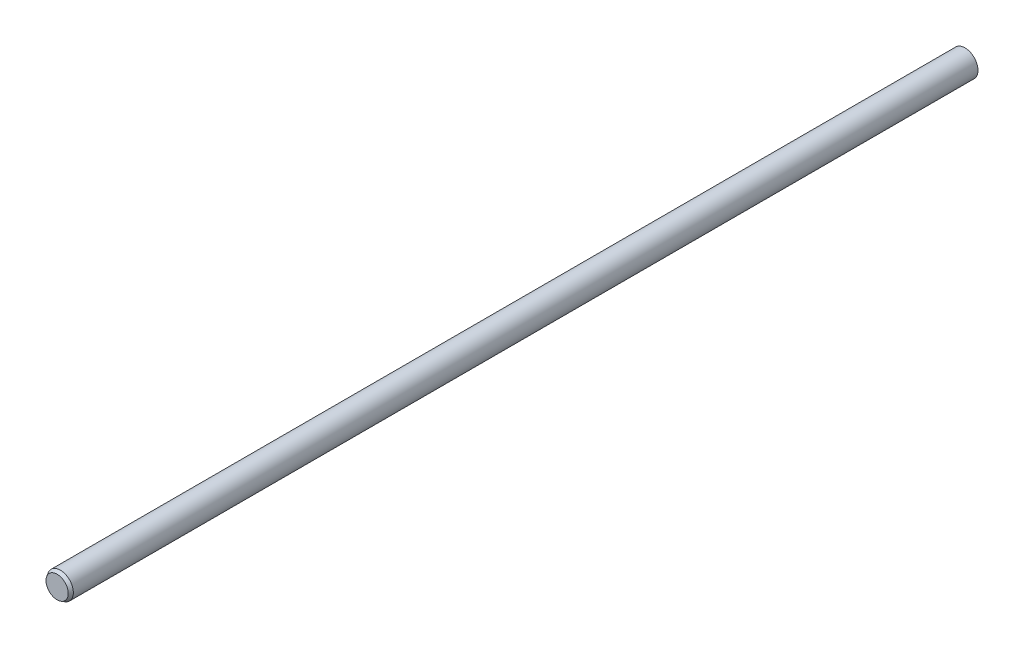
SolidWorks part; units mm, degrees
material "1060 Alloy"
ref_plane "Front Plane" through (0, 0, 0) normal (0, 0, 1) x (1, 0, 0)
ref_plane "Top Plane" through (0, 0, 0) normal (0, 1, 0) x (1, 0, 0)
ref_plane "Right Plane" through (0, 0, 0) normal (1, 0, 0) x (0, 0, -1)
sketch "Sketch1" plane through (0, 0, 0) normal (0, 0, 1) x (1, 0, 0)
  circle A0 centre (0, 0) radius 4
extrude "Boss-Extrude1" add sketch "Sketch1" along normal blind 280
chamfer "Chamfer1" distance 1 angle 30 2 edges at (4, 0, 280) (4, 0, 0)
